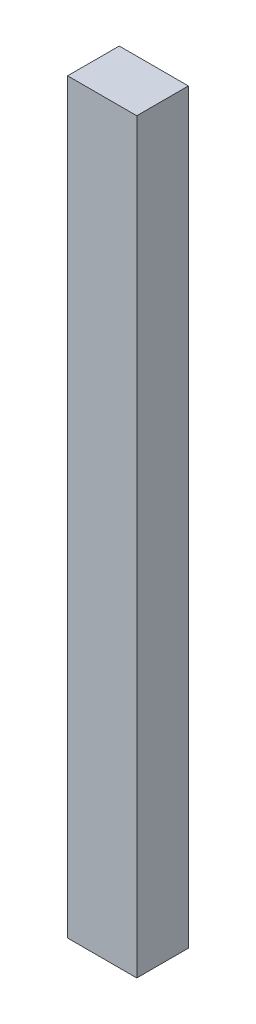
SolidWorks part; units mm, degrees
ref_plane "Front Plane" through (0, 0, 0) normal (0, 0, 1) x (1, 0, 0)
ref_plane "Top Plane" through (0, 0, 0) normal (0, 1, 0) x (1, 0, 0)
ref_plane "Right Plane" through (0, 0, 0) normal (1, 0, 0) x (0, 0, -1)
sketch "Sketch1" plane through (0, 0, 0) normal (0, 1, 0) x (1, 0, 0)
  line L0 (-27.8321, 19.4041) -> (30.9681, 19.4041)
  line L1 (30.9681, 19.4041) -> (30.9681, -24.5001)
  line L2 (30.9681, -24.5001) -> (-27.8321, -24.5001)
  line L3 (-27.8321, -24.5001) -> (-27.8321, 19.4041)
extrude "Boss-Extrude1" add sketch "Sketch1" along normal blind 635
